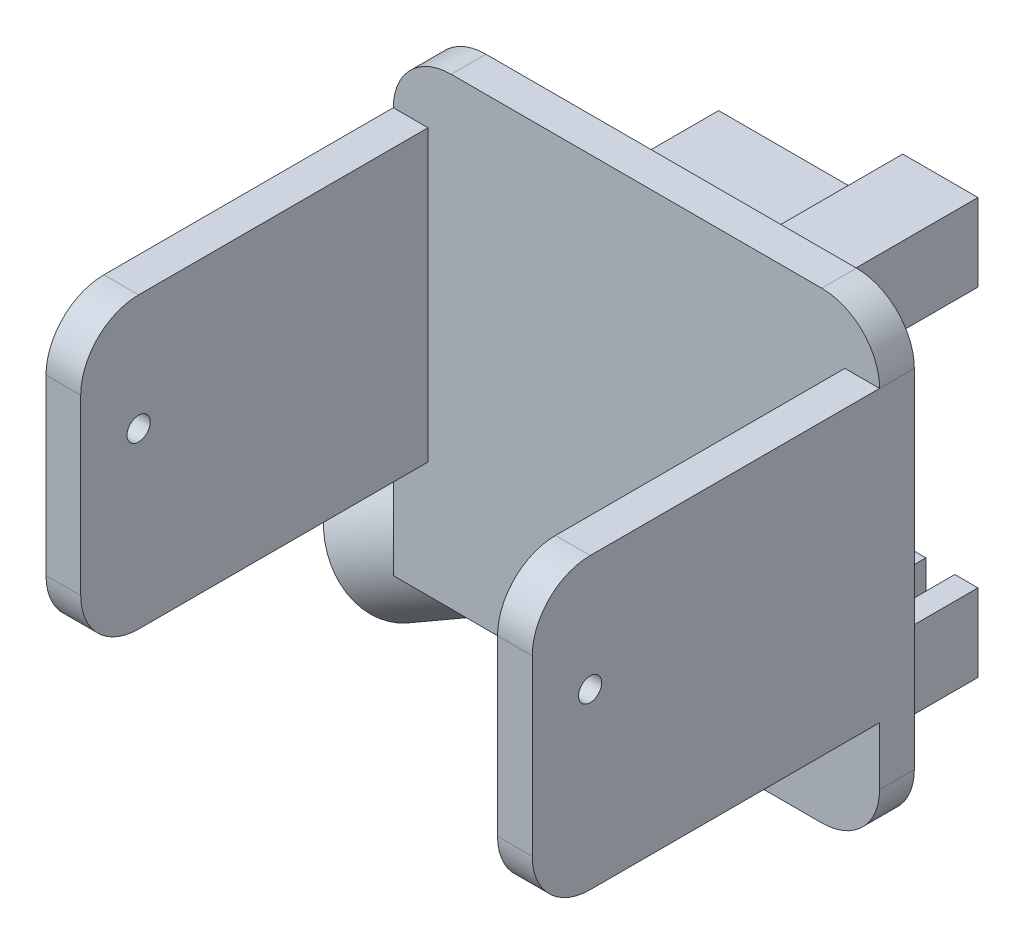
SolidWorks part; units mm, degrees
ref_plane "Front Plane" through (0, 0, 0) normal (0, 0, 1) x (1, 0, 0)
ref_plane "Top Plane" through (0, 0, 0) normal (0, 1, 0) x (1, 0, 0)
ref_plane "Right Plane" through (0, 0, 0) normal (1, 0, 0) x (0, 0, -1)
sketch "Sketch1" plane through (0, 0, 0) normal (0, 0, 1) x (1, 0, 0)
  line L0 (0, 0) -> (0, 22.5)
  line L1 (0, 22.5) -> (15.9, 22.5)
  line L2 (15.9, 22.5) -> (15.9, 27.2)
  line L3 (15.9, 27.2) -> (18.4, 27.2)
  line L4 (18.4, 27.2) -> (18.4, 22.5)
  line L5 (18.4, 22.5) -> (26.7, 22.5)
  line L6 (26.7, 22.5) -> (26.7, 17.767)
  line L7 (26.7, 17.767) -> (29.9, 17.767)
  line L8 (29.9, 17.767) -> (29.9, 13.167)
  line L9 (29.9, 13.167) -> (26.7, 13.167)
  line L10 (26.7, 13.167) -> (26.7, 7.8)
  line L11 (26.7, 7.8) -> (22.7, 7.8)
  line L12 (22.7, 7.8) -> (22.7, 0)
  line L13 (22.7, 0) -> (18.4, 0)
  line L14 (18.4, 0) -> (18.4, -4.7)
  line L15 (18.4, -4.7) -> (15.9, -4.7)
  line L16 (15.9, -4.7) -> (15.9, 0)
  line L17 (15.9, 0) -> (5.7, 0)
  line L27 (20.4, -2) -> (20.4, -6.7)
  line L28 (20.4, -6.7) -> (13.9, -6.7)
  line L29 (13.9, -6.7) -> (13.9, -2)
  line L30 (13.9, -2) -> (5.7, -2)
  line L31 (-2, -2) -> (-2, 24.5)
  line L32 (-2, 24.5) -> (13.9, 24.5)
  line L33 (13.9, 24.5) -> (13.9, 29.2)
  line L34 (13.9, 29.2) -> (20.4, 29.2)
  line L35 (20.4, 29.2) -> (20.4, 24.5)
  line L36 (20.4, 24.5) -> (20.4, 22.5)
  line L37 (20.4, -2) -> (20.4, 0)
  line L38 (5.7, 0) -> (5.7, -2)
  line L39 (4.5, 0) -> (4.5, -2)
  line L40 (4.5, 0) -> (0, 0)
  line L41 (15.9, 0) -> (0, 0) construction
  line L42 (4.5, -2) -> (-2, -2)
  line L43 (13.9, -2) -> (-2, -2) construction
  line L44 (20.4, 24.5) -> (28.7, 24.5) construction
  line L45 (28.7, 24.5) -> (28.7, 19.767) construction
  line L46 (28.7, 19.767) -> (31.9, 19.767) construction
  line L47 (31.9, 19.767) -> (31.9, 11.167) construction
  line L48 (31.9, 11.167) -> (28.7, 11.167) construction
  line L49 (28.7, 11.167) -> (28.7, 5.8) construction
  line L50 (28.7, 5.8) -> (24.7, 5.8) construction
  line L51 (24.7, 5.8) -> (24.7, -2) construction
  line L52 (24.7, -2) -> (20.4, -2) construction
  point P17 (4.5, 0)
  point P20 (5.7, 0)
  dimension "D1" = 15.9
  dimension "D2" = 22.5
  dimension "D3" = 2.5
  dimension "D4" = 15.9
  dimension "D5" = 2.5
  dimension "D6" = 4.7
  dimension "D7" = 4.7
  dimension "D8" = 4.7
  dimension "D9" = 22.7
  dimension "D10" = 26.7
  dimension "D11" = 7.8
  dimension "D12" = 3.2
  dimension "D13" = 4.6
  dimension "D14" = 3.2
  dimension "D15" = 4.5
  dimension "D16" = 1.2
  dimension "D17" = 2
extrude "Boss-Extrude1" add sketch "Sketch1" along normal blind 11.8 contours L42 L39 L40 L0 L1 L2 L3 L4 L5 L36 L35 L34 L33 L32 L31 | L17 L38 L30 L29 L28 L27 L37 L13 L14 L15 L16
sketch "Sketch2" plane through (0, 0, 11.8) normal (0, 0, 1) x (1, 0, 0)
  line L0 (29.9, 17.767) -> (29.9, 13.167) construction
  line L1 (26.7, 36.5628) -> (26.7, -11.7731)
  line L2 (26.7, 22.5) -> (26.7, 17.767) construction
  line L4 (26.7, 36.5628) -> (-38.9996, 36.5628)
  line L5 (26.7, 36.5628) -> (26.7, -56.1622)
  line L6 (26.7, -56.1622) -> (-38.9996, -56.1622)
  line L7 (-38.9996, 36.5628) -> (-38.9996, -56.1622)
  point P0 (29.9, 15.467)
  line M1 (-2, -2) -> (4.5, -2)
  line M2 (4.5, -2) -> (4.5, 0)
  line M3 (4.5, 0) -> (0, 0)
  line M4 (0, 0) -> (0, 22.5)
  line M5 (0, 22.5) -> (15.9, 22.5)
  line M6 (15.9, 22.5) -> (15.9, 27.2)
  line M7 (15.9, 27.2) -> (18.4, 27.2)
  line M8 (18.4, 27.2) -> (18.4, 22.5)
  line M9 (18.4, 22.5) -> (20.4, 22.5)
  line M10 (20.4, 22.5) -> (20.4, 29.2)
  line M11 (20.4, 29.2) -> (13.9, 29.2)
  line M12 (13.9, 29.2) -> (13.9, 24.5)
  line M13 (13.9, 24.5) -> (-2, 24.5)
  line M14 (-2, 24.5) -> (-2, -2)
extrude "Boss-Extrude2" add sketch "Sketch2" along normal blind 3 contours L4 L7 L6 L5 L1 M1 M14 M13 M12 M11 M10 M9 M8 M7 M6 M5 M4 M3 M2 | M14 M1 M2 M3 M4 M5 M6 M7 M8 M9 M10 M11 M12 M13
sketch "Sketch3" plane through (0, 0, 14.8) normal (0, 0, 1) x (1, 0, 0)
  line L0 (26.7, 36.5628) -> (-38.9996, 36.5628) construction
  line L1 (26.7, 36.5628) -> (26.7, -56.1622) construction
  line L2 (26.7, 30.467) -> (-38.9996, 30.467)
  line L3 (-38.9996, 36.5628) -> (-38.9996, -56.1622) construction
  line L4 (26.7, -9.533) -> (-38.9996, -9.533)
  line L6 (26.7, 25.467) -> (23.7, 25.467)
  line L7 (26.7, 25.467) -> (26.7, 0.467)
  line L8 (26.7, 0.467) -> (23.7, 0.467)
  line L9 (23.7, 25.467) -> (23.7, 0.467)
  line L10 (-15.3, 25.467) -> (-12.3, 25.467)
  line L11 (-15.3, 25.467) -> (-15.3, 0.467)
  line L12 (-15.3, 0.467) -> (-12.3, 0.467)
  line L13 (-12.3, 25.467) -> (-12.3, 0.467)
  point P0 (-15.3, 36.5628)
  point P6 (26.7, 15.467)
  point P7 (26.7, 30.467)
  point P8 (26.7, -9.533)
  line M8 (26.7, -56.1622) -> (26.7, 36.5628)
  dimension "D1" = 42
  dimension "D2" = 15
  dimension "D3" = 25
  dimension "D4" = 3
  dimension "D5" = 25
  dimension "D6" = 5
  dimension "D7" = 36
  dimension "D8" = 3
  dimension "D9" = 25
extrude "Boss-Extrude3" add sketch "Sketch3" along normal blind 30 contours L13 L10 L11 L12 | L6 L9 L8 M8
sketch "Sketch4" plane through (26.7, 0, 0) normal (1, 0, 0) x (0, 0, -1)
  circle A0 centre (-39.8, 15.467) radius 1
  point P0 (-39.8, 15.467)
  dimension "D1" = 25
extrude "Cut-Extrude1" cut sketch "Sketch4" against normal blind 53
fillet "Fillet1" radius 5 4 edges at (-13.8, 0.467, 44.8) (25.2, 0.467, 44.8) (25.2, 25.467, 44.8) (-13.8, 25.467, 44.8)
sketch "Sketch5" plane through (0, 0, 11.8) normal (0, 0, -1) x (-1, 0, 0)
  line L0 (2, -2) -> (15.0476, -9.533)
  line L1 (-26.7, -9.533) -> (38.9996, -9.533) construction
ref_plane "Plane1" through (-2.366, -1.366, 0) normal (-0.866, -0.5, 0) x (0, 0, 1)
sketch "Sketch6" plane through (-2.366, -1.366, 0) normal (-0.866, -0.5, 0) x (0, 0, 1)
  line L0 (11.8, -0.7321) -> (0, -0.7321) construction
  circle A0 centre (5.9, -0.7321) radius 5.9
  circle A1 centre (5.9, -0.7321) radius 5
  dimension "D1" = 11.8
extrude "Boss-Extrude7" add sketch "Sketch6" along normal blind 25 separate body
sketch "Sketch8" plane through (0, 0, 11.8) normal (0, 0, -1) x (-1, 0, 0)
  line L1 (-29.0309, 30.467) -> (42.5329, 30.467)
  line L2 (-29.0309, 30.467) -> (-29.0309, 38.3466)
  line L3 (-29.0309, 38.3466) -> (42.5329, 38.3466)
  line L4 (42.5329, 30.467) -> (42.5329, 38.3466)
  line L5 (-29.0309, -9.533) -> (42.5329, -9.533)
  line L6 (-29.0309, -9.533) -> (-29.0309, -63.3789)
  line L7 (-29.0309, -63.3789) -> (42.5329, -63.3789)
  line L8 (42.5329, -9.533) -> (42.5329, -63.3789)
extrude "Cut-Extrude2" cut sketch "Sketch8" against normal blind 25
sketch "Sketch9" plane through (0, 0, 14.8) normal (0, 0, 1) x (1, 0, 0)
  line L0 (26.7, -9.533) -> (-38.9996, -9.533) construction
  line L1 (-38.9996, 30.467) -> (-15.3, 30.467)
  line L2 (-38.9996, 30.467) -> (-38.9996, -9.533)
  line L3 (-38.9996, -9.533) -> (-15.3, -9.533)
  line L4 (-15.3, 30.467) -> (-15.3, -9.533)
  line L5 (-15.3, 25.467) -> (-15.3, 0.467) construction
extrude "Cut-Extrude3" cut sketch "Sketch9" against normal blind 3
fillet "Fillet2" radius 5 3 edges at (26.7, -9.533, 13.3) (26.7, 30.467, 13.3) (-15.3, 30.467, 13.3)
